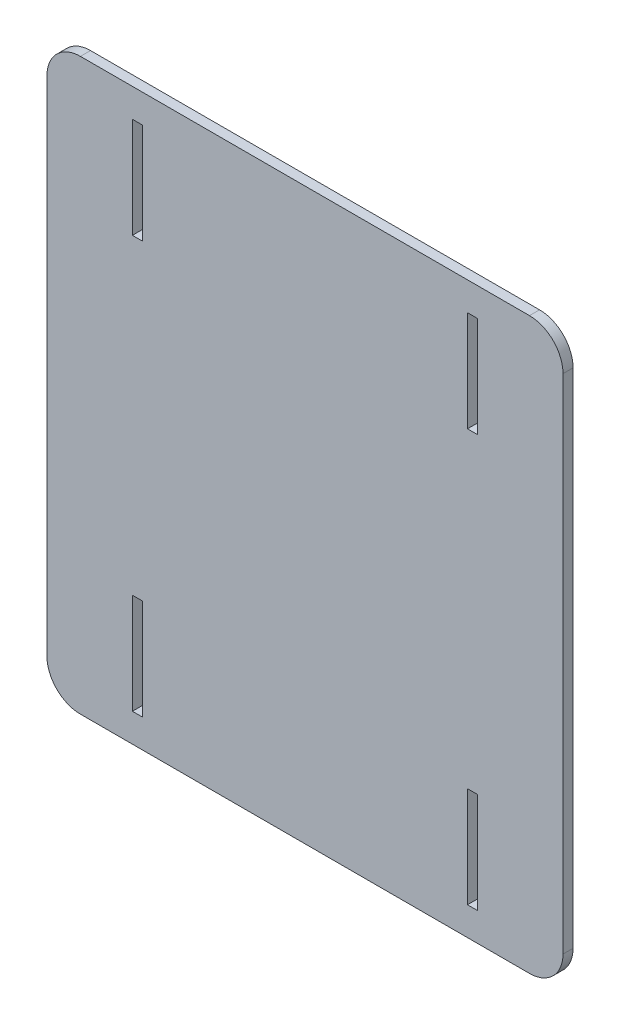
SolidWorks part; units mm, degrees
ref_plane "Plano frontal" through (0, 0, 0) normal (0, 0, 1) x (1, 0, 0)
ref_plane "Plano superior" through (0, 0, 0) normal (0, 1, 0) x (1, 0, 0)
ref_plane "Plano direito" through (0, 0, 0) normal (1, 0, 0) x (0, 0, -1)
sketch "Esboço1" plane through (0, 0, 0) normal (0, 0, 1) x (1, 0, 0)
  line L1 (-77, -85) -> (77, -85)
  line L2 (-77, -85) -> (-77, 85)
  line L3 (-77, 85) -> (77, 85)
  line L4 (77, -85) -> (77, 85)
  line L5 (-77, -85) -> (77, 85) construction
  line L6 (-77, 85) -> (77, -85) construction
  point P0 (0, 0)
  dimension "D1" = 154
  dimension "D2" = 170
extrude "Ressalto-extrusão1" add sketch "Esboço1" along normal blind 3
fillet "Filete1" radius 10 4 edges at (77, 85, 1.5) (77, -85, 1.5) (-77, -85, 1.5) (-77, 85, 1.5)
sketch "Esboço2" plane through (0, 0, 3) normal (0, 0, 1) x (1, 0, 0)
  line L0 (-51.5, 46.5) -> (-48.5, 46.5)
  line L1 (-51.5, -76.5) -> (51.5, -76.5) construction
  line L2 (-51.5, -76.5) -> (-51.5, 76.5) construction
  line L3 (-51.5, 76.5) -> (51.5, 76.5) construction
  line L4 (51.5, -76.5) -> (51.5, 76.5) construction
  line L5 (-51.5, -76.5) -> (51.5, 76.5) construction
  line L6 (-51.5, 76.5) -> (51.5, -76.5) construction
  line L7 (-51.5, 76.5) -> (-48.5, 76.5)
  line L8 (-51.5, 76.5) -> (-51.5, -76.5)
  line L9 (-51.5, -76.5) -> (-48.5, -76.5)
  line L10 (-48.5, 76.5) -> (-48.5, -76.5)
  line L11 (51.5, 76.5) -> (48.5, 76.5)
  line L12 (51.5, 76.5) -> (51.5, -76.5)
  line L13 (51.5, -76.5) -> (48.5, -76.5)
  line L14 (48.5, 76.5) -> (48.5, -76.5)
  line L15 (48.5, 46.5) -> (51.5, 46.5)
  line L16 (-51.5, -46.5) -> (-48.5, -46.5)
  line L17 (48.5, -46.5) -> (51.5, -46.5)
  point P0 (0, 0)
  dimension "D1" = 153
  dimension "D2" = 103
  dimension "D3" = 3
  dimension "D4" = 30
  dimension "D5" = 30
extrude "Corte-extrusão1" cut sketch "Esboço2" against normal through all contours L10 L7 L8 L0 | L14 L15 L12 L11 | L17 L14 L13 L12 | L16 L8 L9 L10
